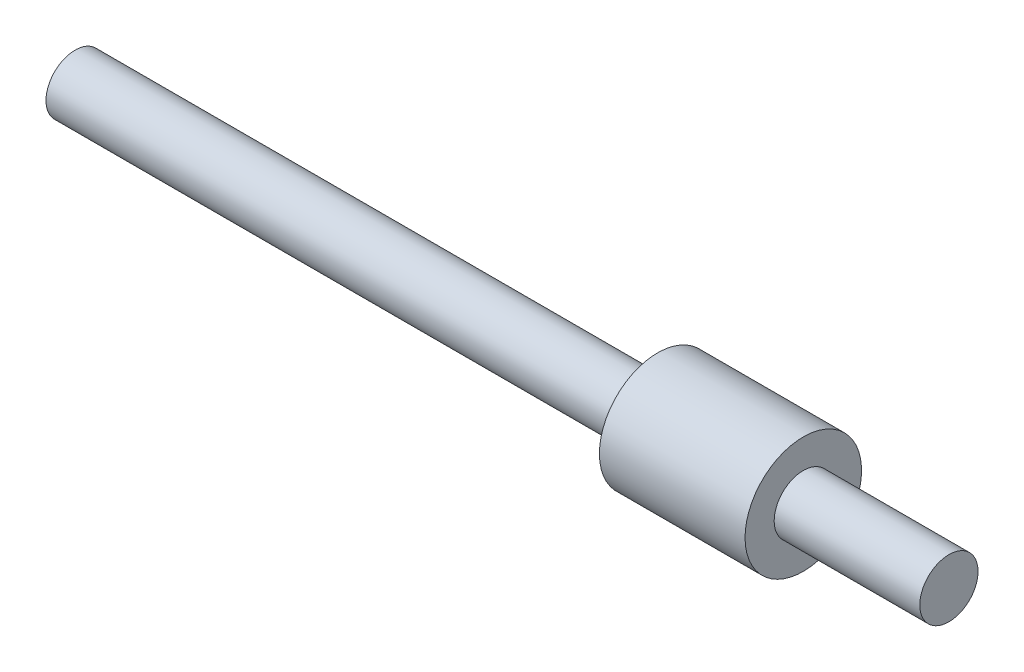
SolidWorks part; units mm, degrees
ref_plane "Płaszczyzna przednia" through (0, 0, 0) normal (0, 0, 1) x (1, 0, 0)
ref_plane "Płaszczyzna górna" through (0, 0, 0) normal (0, 1, 0) x (1, 0, 0)
ref_plane "Płaszczyzna prawa" through (0, 0, 0) normal (1, 0, 0) x (0, 0, -1)
sketch "Szkic1" plane through (0, 0, 0) normal (0, 0, 1) x (1, 0, 0)
  line L0 (0, 0) -> (150, 0) construction
  line L1 (0, 0) -> (0, 5)
  line L2 (0, 5) -> (100, 5)
  line L3 (100, 5) -> (100, 10)
  line L4 (100, 10) -> (125, 10)
  line L5 (125, 10) -> (125, 5)
  line L6 (125, 5) -> (150, 5)
  line L7 (150, 5) -> (150, 0)
  line L8 (0, 0) -> (150, 0)
  point P7 (120.1181, 0)
  point P10 (108.4045, 5)
  point P11 (0, 4.0771)
  dimension "D1" = 10
  dimension "D2" = 100
  dimension "D3" = 25
  dimension "D4" = 25
  dimension "D5" = 20
revolve "Obrót1" add sketch "Szkic1" angle 360 about L0
